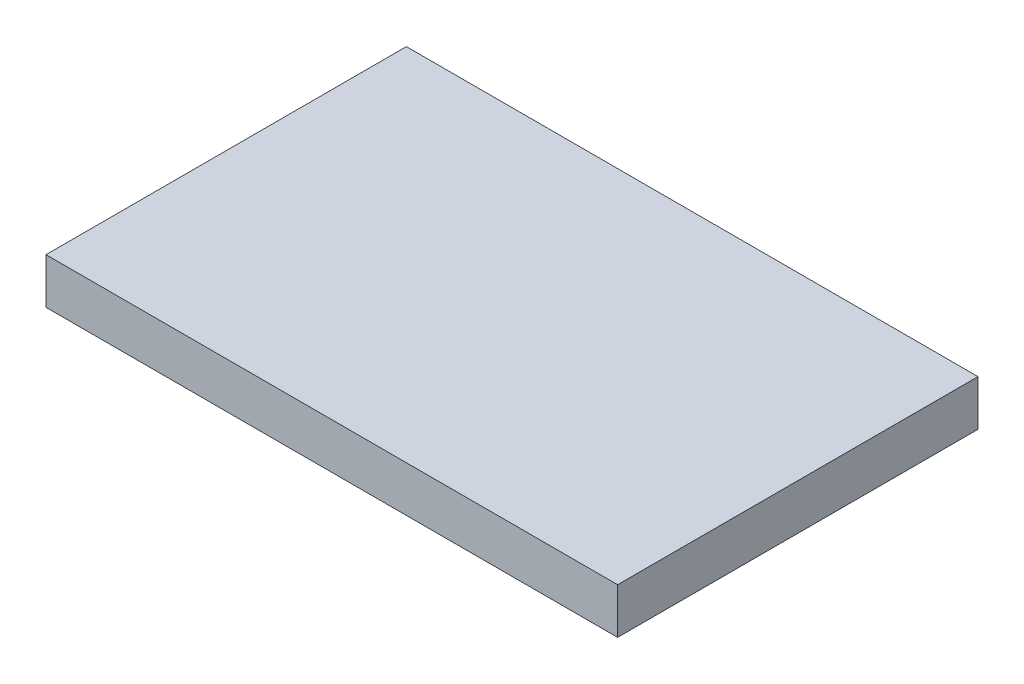
SolidWorks part; units mm, degrees
ref_plane "Plan de face" through (0, 0, 0) normal (0, 0, 1) x (1, 0, 0)
ref_plane "Plan de dessus" through (0, 0, 0) normal (0, 1, 0) x (1, 0, 0)
ref_plane "Plan de droite" through (0, 0, 0) normal (1, 0, 0) x (0, 0, -1)
sketch "Esquisse1" plane through (0, 0, 0) normal (0, 1, 0) x (1, 0, 0)
  line L5 (6.075, -3.83) -> (-6.075, -3.83)
  line L6 (6.075, -3.83) -> (6.075, 3.83)
  line L7 (6.075, 3.83) -> (-6.075, 3.83)
  line L8 (-6.075, -3.83) -> (-6.075, 3.83)
  line L9 (6.075, -3.83) -> (-6.075, 3.83) construction
  line L10 (6.075, 3.83) -> (-6.075, -3.83) construction
  point P0 (0, 0)
  dimension "D1" = 12.15
  dimension "D2" = 7.66
extrude "Boss.-Extru.1" add sketch "Esquisse1" along normal blind 0.97
